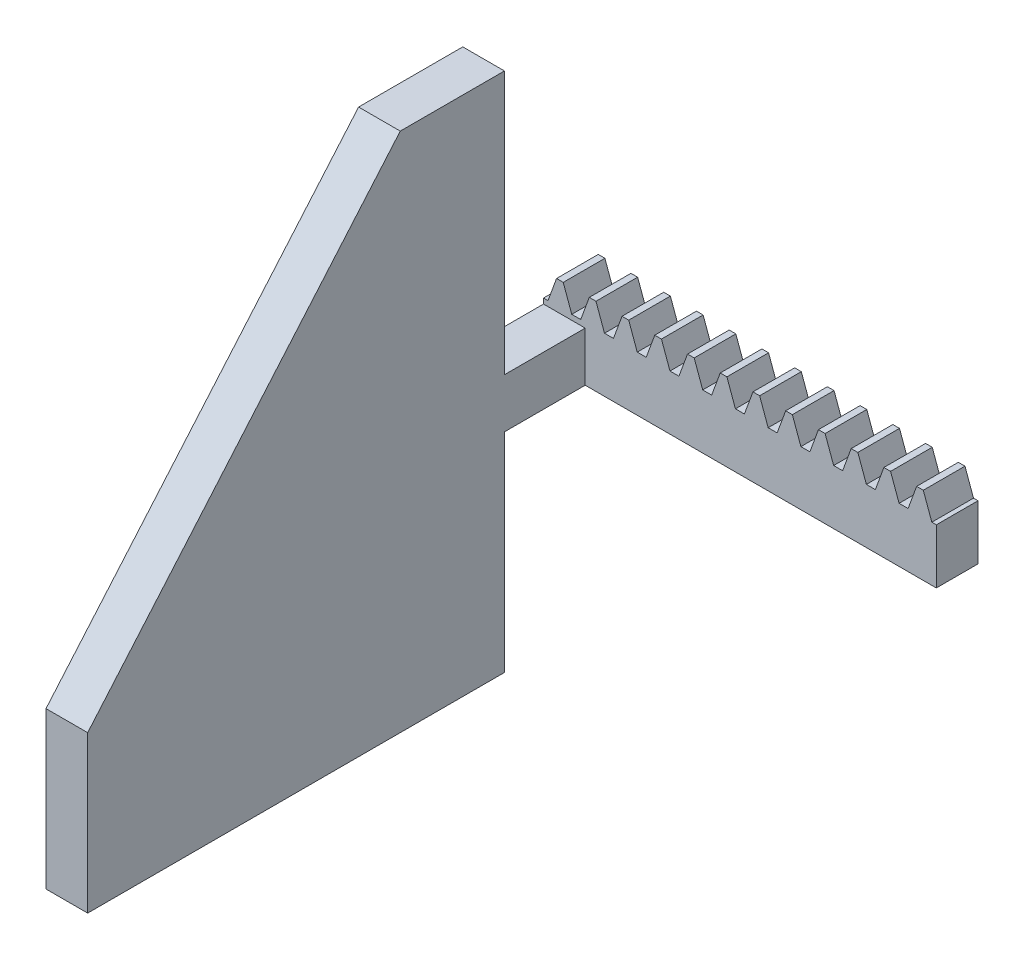
SolidWorks part; units mm, degrees
extrude "Blank" add sketch "BlankSke" against normal blind 8
sketch "BlankSke" plane through (0, 0, 0) normal (0, 0, 1) x (1, 0, 0)
  line L1 (0, 0) -> (120, 0)
  line L2 (0, 0) -> (0, 16)
  line L3 (0, 16) -> (120, 16)
  line L4 (120, 0) -> (120, 16)
  dimension "Length" = 120
  dimension "Blank_height" = 16
ref_plane "Plane1" through (0, 0, 0) normal (0, 0, 1) x (1, 0, 0)
ref_plane "Plane2" through (0, 0, 0) normal (0, 1, 0) x (1, 0, 0)
ref_plane "Plane3" through (0, 0, 0) normal (1, 0, 0) x (0, 0, -1)
sketch "HoldingSke" plane through (0, 0, 0) normal (0, 1, 0) x (1, 0, 0)
  line L0 (0, 0) -> (0.0696, 0.4951)
  line L1 (-15, 0) -> (100, 0) construction
  line L2 (0, 0) -> (-2.1039, 2.3779)
  line L3 (0, 0) -> (-11.863, 4.5341)
  line L4 (0, 0) -> (8.0624, 3.0949)
  line L5 (0, 0) -> (-23.7986, -8.8762)
  line L6 (0, 0) -> (-10.5278, -7.1032)
  line L9 (-71.009, 38.7566) -> (41.7541, 79.799)
  line L10 (-76.2, 4.3779) -> (-62.2, 4.3779)
  line L11 (0, 0) -> (-8, 0)
  line L12 (-76.2, 101.6) -> (-76.133, 101.6)
  line L13 (24.9733, 27.94) -> (52.9518, 28.4284)
  line L14 (24.9733, 27.94) -> (24.9743, 27.94)
  line L15 (24.9733, 27.94) -> (100.4006, 29.5858)
  circle A0 centre (0, 0) radius 19.05
  circle A1 centre (0, 0) radius 7
  circle A2 centre (0, 0) radius 12.7
  dimension "MPH" = 14
  dimension "Diameter" = 38.1
  dimension "Num_teeth" = 21
  dimension "Pitch" = 0.5
  dimension "Show_teeth" = 998
  dimension "Thickness" = 12.7
  dimension "Ap" = 20
  dimension "Pitch_height" = 14
  dimension "Width" = 8
  dimension "Backlash" = 0.067
  dimension "Addendum_fac" = 1
  dimension "Dedendum_fac" = 1.25
  dimension "Clearance_fac" = 0.25
  dimension "Dedendum_add" = 0.001
  dimension "Length" = 120
  dimension "Module" = 2
sketch "TooCutSkeIll" plane through (0, 0, 0) normal (0, 0, 1) x (1, 0, 0)
  line L0 (-2.4806, 15.9474) -> (-0.9819, 11.8296)
  line L1 (-0.5111, 11.5) -> (0.5111, 11.5)
  line L2 (0.9819, 11.8296) -> (2.4806, 15.9474)
  line L3 (120, 16) -> (0, 16) construction
  line L4 (0, 0) -> (0, 64.897) construction
  line L5 (-13.208, 14) -> (12.954, 14) construction
  line L6 (0, 0) -> (120, 0) construction
  line L7 (1.7718, 14) -> (1.7718, 48.7463) construction
  line L8 (-1.7718, 14) -> (-1.7718, 48.7463) construction
  line L9 (2.5558, 16) -> (2.5558, 16.0254)
  line L10 (-2.5558, 16) -> (-2.5558, 16.0254)
  line L11 (-2.5558, 16.0254) -> (2.5558, 16.0254)
  arc A0 (0.5111, 11.5) -> (0.9819, 11.8296) centre (0.5111, 12.001) ccw
  arc A1 (-0.9819, 11.8296) -> (-0.5111, 11.5) centre (-0.5111, 12.001) ccw
  arc A2 (2.5558, 16) -> (2.4806, 15.9474) centre (2.5558, 15.92) ccw
  arc A3 (-2.4806, 15.9474) -> (-2.5558, 16) centre (-2.5558, 15.92) ccw
  dimension "Pitch_height" = 14
  dimension "Addendum_plus" = 2.0254
  dimension "Pressure_angle" = 20
  dimension "Gap_width" = 3.5436
  dimension "Dedendum" = 2.5
extrude "ToothCutIll" [suppressed] cut sketch "TooCutSkeIll" against normal through all
sketch "TooCutSkeSim" plane through (0, 0, 0) normal (0, 0, 1) x (1, 0, 0)
  line L0 (0.8619, 11.5) -> (-0.8619, 11.5)
  line L1 (2.509, 16.0254) -> (0.8619, 11.5)
  line L2 (0, 17.4625) -> (0, 53.467) construction
  line L3 (2.509, 16.0254) -> (-2.509, 16.0254)
  line L6 (-2.509, 16.0254) -> (-0.8619, 11.5)
  line L9 (-1.7718, 14) -> (1.7718, 14) construction
  line L10 (0, 0) -> (120, 0) construction
  line L11 (1.7718, 14) -> (1.7718, 53.467) construction
  line L12 (-1.7718, 14) -> (-1.7718, 53.467) construction
  dimension "Pitch_height" = 14
  dimension "Addendum_plus" = 2.0254
  dimension "Pressure_angle" = 20
  dimension "Gap_width" = 3.5436
  dimension "Dedendum" = 2.5
extrude "ToothCutSim" cut sketch "TooCutSkeSim" against normal through all
pattern_linear "TeethCuts" count 20 spacing 6.2832 along (1, 0, 0) of "ToothCutIll", "ToothCutSim"
sketch "Sketch1" plane through (120, 0, 0) normal (1, 0, 0) x (0, 0, -1)
  line L0 (0, 1) -> (8, 1)
  line L1 (0, 0) -> (0, 11.5) construction
  line L2 (8, 0) -> (8, 11.5) construction
  line L3 (8, 1) -> (8, 0)
  line L4 (8, 0) -> (0, 0)
  line L5 (0, 0) -> (0, 1)
  dimension "D1" = 1
extrude "Cut-Extrude1" cut sketch "Sketch1" against normal through all
sketch "Sketch2" plane through (120, 0, 0) normal (1, 0, 0) x (0, 0, -1)
  line L0 (0, 1) -> (-12, 1)
  line L1 (-12, 1) -> (-12, -9)
  line L2 (-12, -9) -> (-122, -9)
  line L3 (-122, -9) -> (-122, 21)
  line L4 (-122, 21) -> (-12, 61)
  line L5 (-12, 61) -> (-12, 10)
  line L6 (-12, 10) -> (0, 10)
  line L7 (0, 1) -> (0, 11.5) construction
  line L8 (0, 10) -> (0, 1)
  dimension "D1" = 110
  dimension "D2" = 30
  dimension "D3" = 9
  dimension "D4" = 70
  dimension "D5" = 10
  dimension "D6" = 12
sketch "Sketch3" plane through (0, 0, 0) normal (-1, 0, 0) x (0, 0, 1)
  line L0 (0, 1) -> (15.5, 1)
  line L1 (15.5, 1) -> (15.5, -39)
  line L5 (15.5, 61) -> (15.5, 10.5)
  line L6 (15.5, 10.5) -> (0, 10.5)
  line L7 (0, 11.5) -> (0, 1) construction
  line L8 (0, 10.5) -> (0, 1)
  line L11 (15.5, -39) -> (95.5, -39)
  line L13 (15.5, 61) -> (35.5, 61)
  line L16 (35.5, 61) -> (95.5, -9)
  line L17 (95.5, -9) -> (95.5, -39)
  dimension "D1" = 9.5
  dimension "D2" = 15.5
  dimension "D3" = 80
  dimension "D4" = 100
  dimension "D6" = 20
  dimension "D8" = 30
extrude "Boss-Extrude2" add sketch "Sketch3" against normal blind 8
sketch "Sketch4" plane through (0, 0, -8) normal (0, 0, -1) x (-1, 0, 0)
  line L0 (-120, 11.5) -> (-118.5186, 11.5)
  line L1 (-113.9592, 11.5) -> (-113.2187, 11.5)
  line L2 (-112.2355, 11.5) -> (-113.9592, 11.5) construction
  line L4 (0, 1) -> (-120, 1) construction
  line L5 (-113.2187, 1) -> (-120, 1)
  line L6 (-120, 1) -> (-120, 11.5)
  line L7 (-118.5186, 11.5) -> (-116.8808, 16)
  line L8 (-116.8808, 16) -> (-115.5971, 16)
  line L9 (-115.5971, 16) -> (-113.9592, 11.5)
  line L10 (-113.2187, 11.5) -> (-112.2355, 11.5)
  line L11 (-112.2355, 11.5) -> (-110.5976, 16)
  line L12 (-110.5976, 16) -> (-109.3139, 16)
  line L13 (-109.3139, 16) -> (-107.676, 11.5)
  line L14 (-107.676, 11.5) -> (-105.9523, 11.5)
  line L15 (-105.9523, 11.5) -> (-104.3144, 16)
  line L16 (-104.3144, 16) -> (-103.0307, 16)
  line L17 (-103.0307, 16) -> (-101.3928, 11.5)
  line L19 (-8, 1) -> (-120, 1) construction
  line L20 (-101.3928, 1) -> (-113.2187, 1)
  line L21 (-101.3928, 11.5) -> (-99.6691, 11.5)
  line L22 (-99.6691, 11.5) -> (-98.0312, 16)
  line L23 (-98.0312, 16) -> (-96.7475, 16)
  line L24 (-96.7475, 16) -> (-95.1097, 11.5)
  line L25 (-95.1097, 11.5) -> (-93.3859, 11.5)
  line L26 (-93.3859, 11.5) -> (-91.748, 16)
  line L27 (-91.748, 16) -> (-90.4643, 16)
  line L28 (-90.4643, 16) -> (-88.8265, 11.5)
  line L29 (-88.8265, 11.5) -> (-87.1027, 11.5)
  line L30 (-87.1027, 11.5) -> (-85.4649, 16)
  line L31 (-85.4649, 16) -> (-84.1811, 16)
  line L32 (-84.1811, 16) -> (-82.5433, 11.5)
  line L33 (-82.5433, 11.5) -> (-80.8195, 11.5)
  line L34 (-80.8195, 11.5) -> (-79.1817, 16)
  line L35 (-79.1817, 16) -> (-77.898, 16)
  line L36 (-77.898, 16) -> (-76.2601, 11.5)
  line L38 (-76.2601, 1) -> (-101.3928, 1)
  line L39 (-76.2601, 11.5) -> (-75.3982, 11.5)
  line L40 (-74.5364, 11.5) -> (-76.2601, 11.5) construction
  line L41 (-75.3982, 11.5) -> (-75.3982, 1)
  line L42 (-75.3982, 1) -> (-76.2601, 1)
  dimension "D1" = 0.7405
extrude "Cut-Extrude2" cut sketch "Sketch4" against normal through all
equation "' \"Module@HoldingSke\" = 6.35"
equation "' \"Num_teeth@HoldingSke\" = 12"
equation "' \"Ap@HoldingSke\" =  20"
equation "' \"Ap@HoldingSke\" = 20"
equation "' \"Width@HoldingSke\" = 0.25 * 25.4"
equation "' \"Show_teeth@HoldingSke\" = 500"
equation "' \"Backlash@HoldingSke\" = 0.009 * 25.4"
equation "' \"Addendum_fac@HoldingSke\" = 1.0"
equation "' \"Dedendum_fac@HoldingSke\" = 1.25"
equation "' \"Dedendum_add@HoldingSke\" = 0.00005 * 25.4"
equation "' \"Clearance_fac@HoldingSke\" = 0.25"
equation "' \"Pitch_height@HoldingSke\" = 1 * 25.4"
equation "' \"Length@HoldingSke\" = 4.71 * 25.4"
equation "\"Pitch@HoldingSke\" = 1 / \"Module@HoldingSke\""
equation "\"MPH@HoldingSke\" = \"Dedendum_fac@HoldingSke\" / \"Pitch@HoldingSke\" + 2 * \"Dedendum_add@HoldingSke\" + 0.002 * 25.4"
equation "\"MPH@HoldingSke\" = ((sgn( \"MPH@HoldingSke\" - \"Pitch_height@HoldingSke\")+1)*( \"MPH@HoldingSke\" - \"Pitch_height@HoldingSke\"))/2 + \"Pitch_height@HoldingSke\""
equation "\"Blank_height@BlankSke\" = \"Pitch_height@HoldingSke\" + \"Addendum_fac@HoldingSke\"  / \"Pitch@HoldingSke\" "
equation "\"Length@BlankSke\" =  \"Length@HoldingSke\""
equation "\"Face_width@Blank\" = \"Width@HoldingSke\""
equation "\"Pressure_angle@TooCutSkeIll\" = \"Ap@HoldingSke\""
equation "\"Addendum_plus@TooCutSkeIll\" =  \"Addendum_fac@HoldingSke\"  / \"Pitch@HoldingSke\" + 0.001 *25.4"
equation "\"Dedendum@TooCutSkeIll\" = \"Dedendum_fac@HoldingSke\"  / \"Pitch@HoldingSke\""
equation "\"Pitch_height@TooCutSkeIll\" =  \"MPH@HoldingSke\""
equation "\"Gap_width@TooCutSkeIll\" = 3.14159265 / 2 / \"Pitch@HoldingSke\" + 6 * \"Backlash@HoldingSke\""
equation "\"Pressure_angle@TooCutSkeSim\" = \"Ap@HoldingSke\""
equation "\"Addendum_plus@TooCutSkeSim\" =  \"Addendum_fac@HoldingSke\"  / \"Pitch@HoldingSke\" + 0.001 * 25.4"
equation "\"Dedendum@TooCutSkeSim\" = \"Dedendum_fac@HoldingSke\"  / \"Pitch@HoldingSke\""
equation "\"Pitch_height@TooCutSkeSim\" =  \"MPH@HoldingSke\""
equation "\"Gap_width@TooCutSkeSim\" = 3.14159265 / 2 / \"Pitch@HoldingSke\" + 6 * \"Backlash@HoldingSke\""
equation "\"Root_fillet@TooCutSkeIll\" = \"Clearance_fac@HoldingSke\" / \"Pitch@HoldingSke\" + \"Dedendum_add@HoldingSke\""
equation "\"Break_rad@TooCutSkeIll\" = 0.02 / \"Pitch@HoldingSke\" * 2"
equation "\"Linear_pitch@TeethCuts\" = 3.14159265 / \"Pitch@HoldingSke\""
equation "\"Num_teeth@HoldingSke\" = int( ( \"Length@HoldingSke\" + 0 ) / (3.14159265 / \"Pitch@HoldingSke\")) + 0.9999  + 1"
equation " \"Num_teeth@TeethCuts\" = int( \"Show_teeth@HoldingSke\" ) + 1"
equation " \"Num_teeth@TeethCuts\" = ((sgn( \"Num_teeth@TeethCuts\" - \"Num_teeth@HoldingSke\" )-1)*( \"Num_teeth@TeethCuts\" - \"Num_teeth@HoldingSke\" ))/-2+ \"Num_teeth@HoldingSke\""
equation " \"Num_teeth@TeethCuts\" = ((sgn( \"Num_teeth@TeethCuts\" - 2.0)+1)*( \"Num_teeth@TeethCuts\" - 2.0))/2 +2.0"
